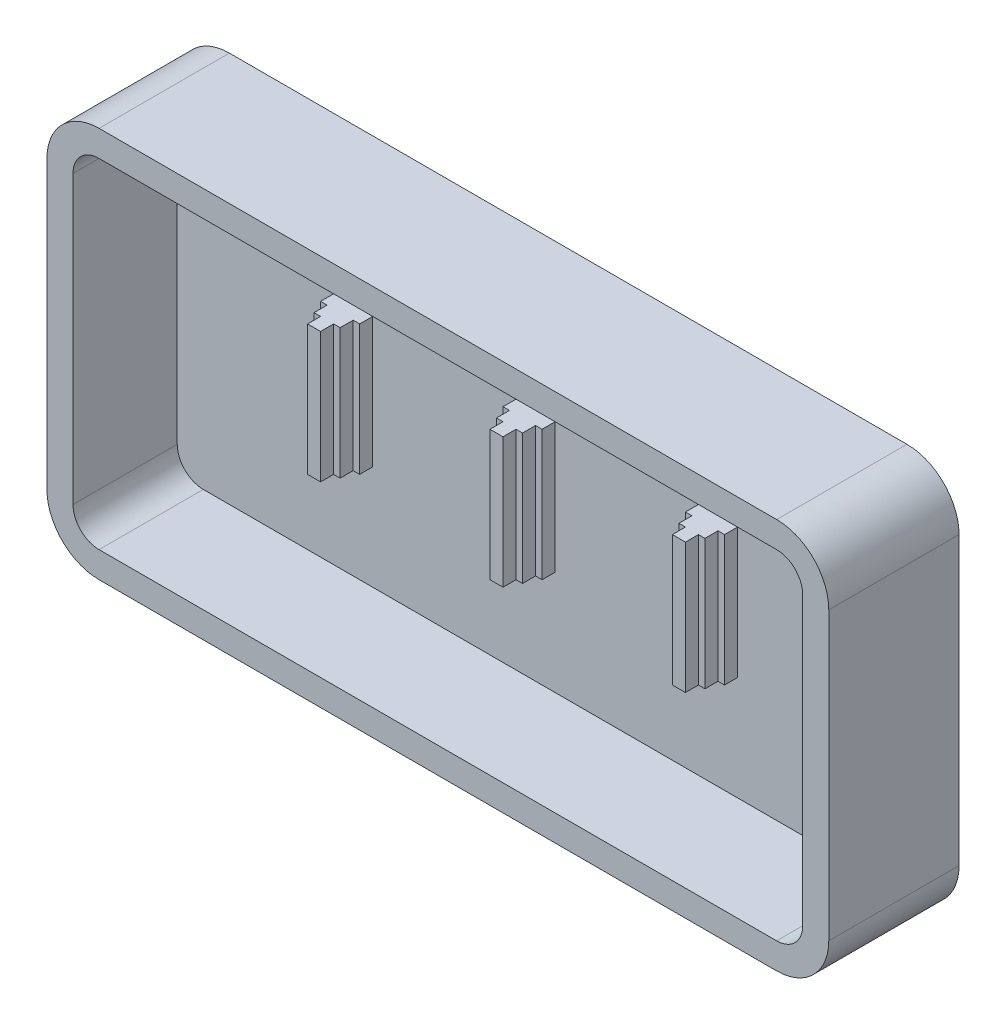
SolidWorks part; units mm, degrees
ref_plane "Front Plane" through (0, 0, 0) normal (0, 0, 1) x (1, 0, 0)
ref_plane "Top Plane" through (0, 0, 0) normal (0, 1, 0) x (1, 0, 0)
ref_plane "Right Plane" through (0, 0, 0) normal (1, 0, 0) x (0, 0, -1)
sketch "Sketch1" plane through (0, 0, 0) normal (0, 0, 1) x (1, 0, 0)
  line L1 (-21.4917, 16.7403) -> (38.5083, 16.7403)
  line L2 (-21.4917, 16.7403) -> (-21.4917, -13.2597)
  line L3 (-21.4917, -13.2597) -> (38.5083, -13.2597)
  line L4 (38.5083, 16.7403) -> (38.5083, -13.2597)
  dimension "D1" = 60
  dimension "D2" = 30
extrude "Boss-Extrude1" add sketch "Sketch1" along normal blind 10
fillet "Fillet1" radius 4 4 edges at (38.5083, 16.7403, 5) (38.5083, -13.2597, 5) (-21.4917, -13.2597, 5) (-21.4917, 16.7403, 5)
shell "Shell1" thickness 2
sketch "Sketch29" plane through (0, 0, 2) normal (0, 0, 1) x (1, 0, 0)
  line L0 (-19.4917, 12.7403) -> (-19.4917, -9.2597) construction
  line L1 (20.5083, 6.7403) -> (23.5083, 6.7403)
  line L2 (20.5083, 6.7403) -> (20.5083, -3.2597)
  line L3 (20.5083, -3.2597) -> (23.5083, -3.2597)
  line L4 (23.5083, 6.7403) -> (23.5083, -3.2597)
  line L5 (34.5083, 14.7403) -> (-17.4917, 14.7403) construction
  line L6 (6.5083, 6.7403) -> (6.5083, -3.2597)
  line L7 (6.5083, 6.7403) -> (9.5083, 6.7403)
  line L8 (9.5083, 6.7403) -> (9.5083, -3.2597)
  line L9 (6.5083, -3.2597) -> (9.5083, -3.2597)
  line L10 (-7.4917, 6.7403) -> (-7.4917, -3.2597)
  line L11 (-7.4917, 6.7403) -> (-4.4917, 6.7403)
  line L12 (-4.4917, 6.7403) -> (-4.4917, -3.2597)
  line L13 (-7.4917, -3.2597) -> (-4.4917, -3.2597)
  dimension "D1" = 10
  dimension "D2" = 3
  dimension "D3" = 40
  dimension "D4" = 8
  dimension "D5" = 3
extrude "Boss-Extrude2" add sketch "Sketch29" along normal blind 1
sketch "Sketch30" plane through (0, 0, 3) normal (0, 0, 1) x (1, 0, 0)
  line L1 (21.0083, -3.2597) -> (23.0083, -3.2597)
  line L2 (21.0083, -3.2597) -> (21.0083, 6.7403)
  line L3 (21.0083, 6.7403) -> (23.0083, 6.7403)
  line L4 (23.0083, -3.2597) -> (23.0083, 6.7403)
  line L6 (20.5083, -3.2597) -> (23.5083, -3.2597) construction
  line L7 (23.5083, 6.7403) -> (20.5083, 6.7403) construction
  line L9 (7.0083, -3.2597) -> (7.0083, 6.7403)
  line L10 (7.0083, -3.2597) -> (9.0083, -3.2597)
  line L11 (9.0083, -3.2597) -> (9.0083, 6.7403)
  line L12 (7.0083, 6.7403) -> (9.0083, 6.7403)
  line L13 (-6.9917, -3.2597) -> (-6.9917, 6.7403)
  line L14 (-6.9917, -3.2597) -> (-4.9917, -3.2597)
  line L15 (-4.9917, -3.2597) -> (-4.9917, 6.7403)
  line L16 (-6.9917, 6.7403) -> (-4.9917, 6.7403)
  dimension "D1" = 10
  dimension "D2" = 2
  dimension "D3" = 0.5
  dimension "D4" = 3
extrude "Boss-Extrude3" add sketch "Sketch30" along normal blind 1
sketch "Sketch31" plane through (0, 0, 4) normal (0, 0, 1) x (1, 0, 0)
  line L1 (21.5083, -3.2597) -> (22.5083, -3.2597)
  line L2 (21.5083, -3.2597) -> (21.5083, 6.7403)
  line L3 (21.5083, 6.7403) -> (22.5083, 6.7403)
  line L4 (22.5083, -3.2597) -> (22.5083, 6.7403)
  line L6 (20.5083, -3.2597) -> (23.5083, -3.2597) construction
  line L7 (23.5083, 6.7403) -> (20.5083, 6.7403) construction
  line L8 (7.5083, -3.2597) -> (7.5083, 6.7403)
  line L9 (7.5083, -3.2597) -> (8.5083, -3.2597)
  line L10 (8.5083, -3.2597) -> (8.5083, 6.7403)
  line L11 (7.5083, 6.7403) -> (8.5083, 6.7403)
  line L12 (-6.4917, -3.2597) -> (-6.4917, 6.7403)
  line L13 (-6.4917, -3.2597) -> (-5.4917, -3.2597)
  line L14 (-5.4917, -3.2597) -> (-5.4917, 6.7403)
  line L15 (-6.4917, 6.7403) -> (-5.4917, 6.7403)
  dimension "D1" = 10
  dimension "D2" = 1
  dimension "D3" = 0.5
  dimension "D4" = 3
extrude "Boss-Extrude4" add sketch "Sketch31" along normal blind 1
